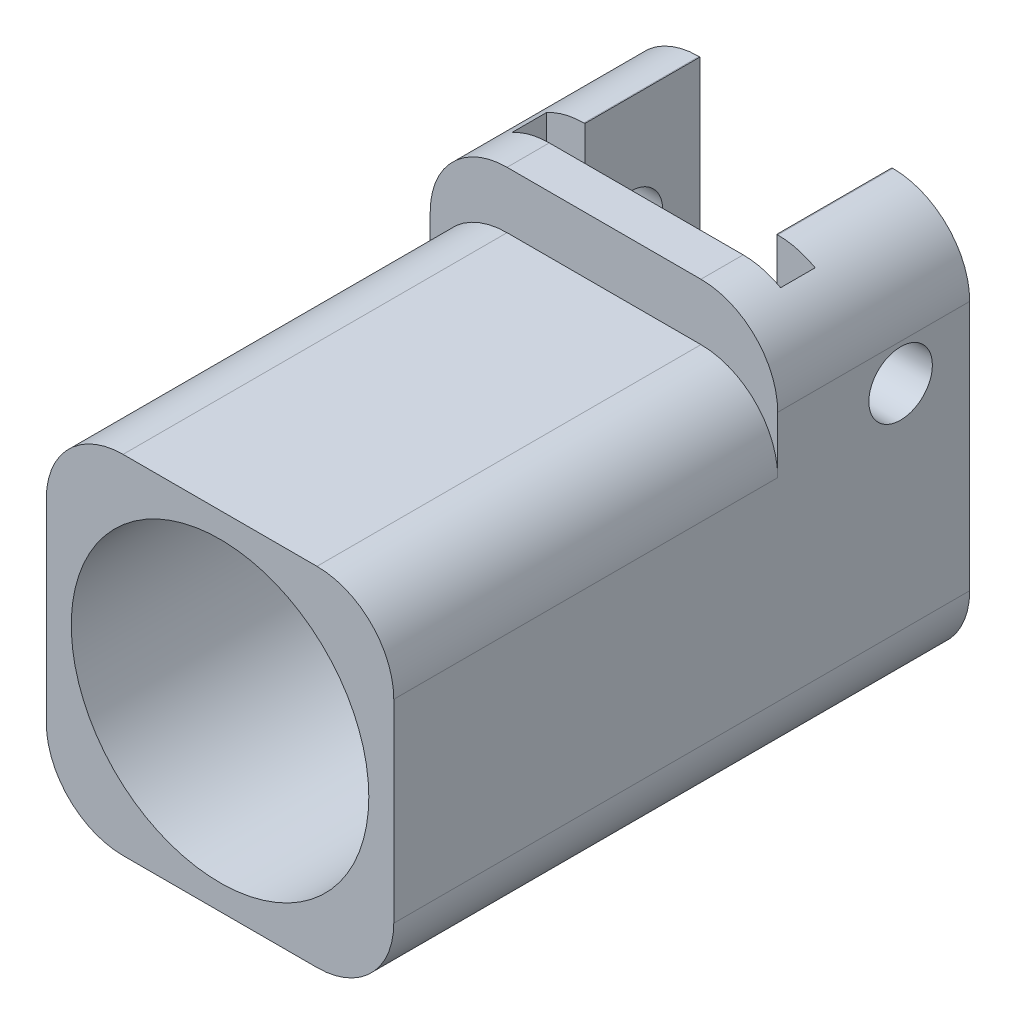
SolidWorks part; units mm, degrees
ref_plane "Front Plane" through (0, 0, 0) normal (0, 0, 1) x (1, 0, 0)
ref_plane "Top Plane" through (0, 0, 0) normal (0, 1, 0) x (1, 0, 0)
ref_plane "Right Plane" through (0, 0, 0) normal (1, 0, 0) x (0, 0, -1)
sketch "Sketch1" plane through (0, 0, 0) normal (0, 0, 1) x (1, 0, 0)
  line L0 (-5.05, 9.05) -> (5.05, 9.05)
  line L1 (9.05, -5.05) -> (9.05, 5.05)
  line L2 (0, 0) -> (0, 14.1446) construction
  line L3 (-9.05, -5.05) -> (-9.05, 5.05)
  line L4 (-12.732, 0) -> (15.0845, 0) construction
  line L5 (-5.05, -9.05) -> (5.05, -9.05)
  arc A4 (5.05, 9.05) -> (9.05, 5.05) centre (5.05, 5.05) cw
  arc A5 (9.05, -5.05) -> (5.05, -9.05) centre (5.05, -5.05) cw
  arc A6 (-5.05, -9.05) -> (-9.05, -5.05) centre (-5.05, -5.05) cw
  arc A7 (-9.05, 5.05) -> (-5.05, 9.05) centre (-5.05, 5.05) cw
  point P11 (9.05, 0)
  point P12 (0, 9.05)
  point P20 (0, -9.05)
  point P21 (-9.05, 0)
  dimension "D3" = 0
  dimension "D1" = 5.05
  dimension "D2" = 5.05
  dimension "D4" = 9.05
  dimension "D5" = 9.05
extrude "Boss-Extrude1" add sketch "Sketch1" along normal blind 30
sketch "Sketch15" plane through (0, 0, 0) normal (0, 0, 1) x (1, 0, 0)
  line L0 (9.05, -5.05) -> (9.05, 5.05) construction
  line L6 (-5.05, -9.05) -> (5.05, -9.05)
  line L7 (-9.05, -5.05) -> (-9.05, 8)
  line L8 (-5.05, 12) -> (5.05, 12)
  line L9 (9.05, -5.05) -> (9.05, 8)
  line L10 (-5.05, -9.05) -> (5.05, -9.05) construction
  line L11 (-9.05, -5.05) -> (-9.05, 5.05) construction
  arc A4 (-5.05, -9.05) -> (-9.05, -5.05) centre (-5.05, -5.05) cw
  arc A5 (5.05, -9.05) -> (9.05, -5.05) centre (5.05, -5.05) ccw
  arc A6 (5.05, 12) -> (9.05, 8) centre (5.05, 8) cw
  arc A7 (-9.05, 8) -> (-5.05, 12) centre (-5.05, 8) cw
  point P0 (0, 0)
  dimension "D2" = 0
  dimension "D5" = 4
  dimension "D1" = 12
  dimension "D3" = 0
  dimension "D4" = 0
extrude "Boss-Extrude3" add sketch "Sketch15" along normal blind 10
sketch "Sketch17" plane through (9.05, 0, 0) normal (1, 0, 0) x (0, 0, -1)
  line L2 (0, -5.05) -> (0, 5.05) construction
  line L3 (-10, 12) -> (0, 12) construction
  circle A0 centre (-3.6, 6.1) radius 1.655
  dimension "D1" = 3.31
  dimension "D2" = 3.6
  dimension "D3" = 5.9
extrude "Cut-Extrude10" cut sketch "Sketch17" against normal blind 30
sketch "Sketch18" plane through (0, 0, 0) normal (0, 0, 1) x (1, 0, 0)
  line L82 (-4.9965, -4.2592) -> (-3.8511, -6.9461)
  line L83 (-3.8511, -6.9461) -> (-2.0485, -4.5591)
  line L86 (-2.0485, -4.5591) -> (-0.5631, -7.2172)
  line L87 (-0.5631, -7.2172) -> (0.9839, -4.6242)
  line L88 (0.9839, -4.6242) -> (2.7048, -7.2172)
  line L91 (2.7048, -7.2172) -> (3.4697, -4.8701)
  line L92 (3.4697, -4.8701) -> (4.6745, -7.0261)
  line L93 (4.6745, -7.0261) -> (4.9982, -5.6687)
  line L94 (-4.9965, -4.2592) -> (-4.9965, 5.3735)
  line L95 (-4.9965, 5.3735) -> (4.9982, 5.3735)
  line L96 (4.9982, 5.3735) -> (4.9982, -5.6687)
  dimension "D1" = 4.9965
  dimension "D2" = 4.9982
extrude "Cut-Extrude11" cut sketch "Sketch18" along normal blind 6
sketch "Sketch20" plane through (0, 0, 6) normal (0, 0, -1) x (-1, 0, 0)
  line L0 (-7, 0) -> (-7, 13.4738)
  line L1 (-7, 13.4738) -> (7, 13.4738)
  line L2 (7, 13.4738) -> (7, 0)
  line L3 (-7, 0) -> (-7, -7.1944)
  line L4 (-7, -7.1944) -> (7, -7.1944)
  line L5 (7, -7.1944) -> (7, 0)
  dimension "D2" = 7
extrude "Cut-Extrude12" cut sketch "Sketch20" against normal blind 1.8
sketch "Sketch21" plane through (0, 0, 0) normal (0, 0, 1) x (1, 0, 0)
  line L0 (-12.732, 0) -> (15.0845, 0) construction
  line L3 (5, 17.4937) -> (-5, 17.4937)
  line L4 (-5, 0) -> (-5, 17.4937)
  line L8 (5, 0) -> (5, -0.5)
  line L9 (5, -0.5) -> (-5, -0.5)
  line L10 (-5, -0.5) -> (-5, 0)
  line L11 (5, 0) -> (5, 17.4937)
  dimension "D1" = 5
  dimension "D2" = 5
  dimension "D3" = 0.5
extrude "Cut-Extrude13" cut sketch "Sketch21" along normal blind 7.2
sketch "Sketch24" plane through (0, 0, 30) normal (0, 0, 1) x (1, 0, 0)
  circle A0 centre (0, 0) radius 7.75
  dimension "D1" = 15.5
extrude "Cut-Extrude15" cut sketch "Sketch24" against normal blind 19
